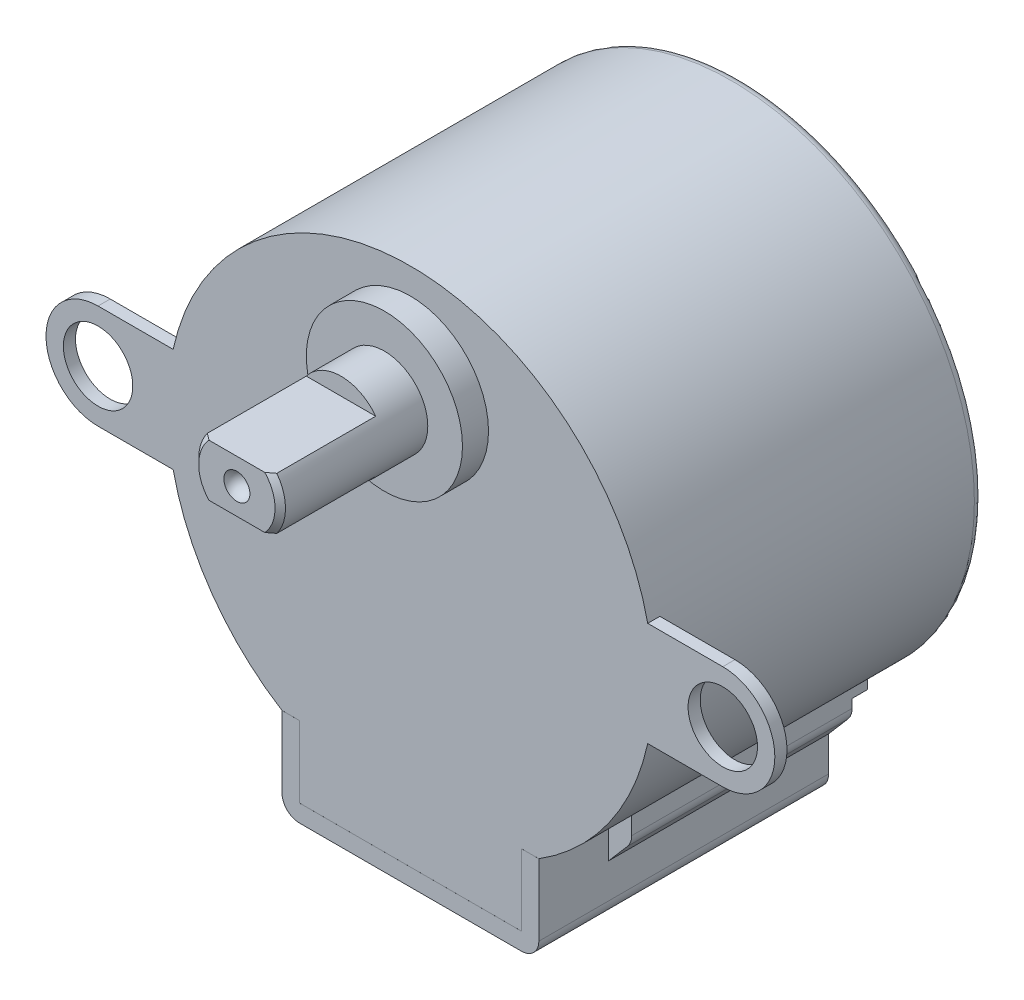
SolidWorks part; units mm, degrees
ref_plane "Ön Düzlem" through (0, 0, 0) normal (0, 0, 1) x (1, 0, 0)
ref_plane "Üst Düzlem" through (0, 0, 0) normal (0, 1, 0) x (1, 0, 0)
ref_plane "Sağ Düzlem" through (0, 0, 0) normal (1, 0, 0) x (0, 0, -1)
sketch "Çizim1" plane through (0, 0, 0) normal (0, 0, 1) x (1, 0, 0)
  circle A0 centre (0, 0) radius 14
  dimension "D1" = 28
extrude "Yükseklik-Ekstrüzyon1" add sketch "Çizim1" along normal blind 19
sketch "Çizim2" plane through (0, 0, 19) normal (0, 0, 1) x (1, 0, 0)
  line L0 (0, 14) -> (0, 8) construction
  circle A0 centre (0, 0) radius 14 construction
  circle A1 centre (0, 8) radius 4.5
  dimension "D2" = 9
  dimension "D1" = 6
extrude "Yükseklik-Ekstrüzyon2" add sketch "Çizim2" along normal blind 1.5
sketch "Çizim3" plane through (0, 0, 20.5) normal (0, 0, 1) x (1, 0, 0)
  circle A0 centre (0, 8) radius 2.5
  dimension "D1" = 5
extrude "Yükseklik-Ekstrüzyon3" add sketch "Çizim3" along normal blind 8.5
sketch "Çizim4" plane through (0, 0, 29) normal (0, 0, 1) x (1, 0, 0)
  line L0 (0, 10.5) -> (0, 9.5) construction
  line L1 (0, 9.5) -> (2.1768, 9.5)
  line L2 (2.1768, 9.5) -> (2.1768, 10.5)
  line L3 (2.1768, 10.5) -> (-2.3997, 10.5)
  line L4 (-2.3997, 10.5) -> (-2.3997, 9.5)
  line L5 (-2.3997, 9.5) -> (0, 9.5)
  line L6 (0, 8) -> (1.2994, 8) construction
  line L7 (2.1768, 5.5) -> (-2.3997, 5.5)
  line L8 (2.1768, 6.5) -> (2.1768, 5.5)
  line L9 (-2.3997, 5.5) -> (-2.3997, 6.5)
  line L10 (-2.3997, 6.5) -> (0, 6.5)
  line L11 (0, 6.5) -> (2.1768, 6.5)
  circle A0 centre (0, 8) radius 2.5 construction
  circle A1 centre (0, 8) radius 2.5 construction
  dimension "D1" = 1
extrude "Kes-Ekstrüzyon1" cut sketch "Çizim4" against normal blind 6
chamfer "Pah1" distance 0.3 angle 45 2 edges at (-2.5, 8, 29) (2.5, 8, 29)
sketch "Çizim5" plane through (0, 0, 29) normal (0, 0, 1) x (1, 0, 0)
  line L0 (0, 8.75) -> (0, 7.25) construction
  line L1 (0, 8.75) -> (0, 7.25)
  arc A0 (0, 7.25) -> (0, 8.75) centre (0, 8) ccw
  dimension "D1" = 1.5
revolve "Kes-Döndür1" cut sketch "Çizim5" angle 360 about L0
sketch "Çizim6" plane through (0, 0, 19) normal (0, 0, 1) x (1, 0, 0)
  line L0 (0, 0) -> (0, -17) construction
  line L1 (0, -17) -> (7.4, -17)
  line L2 (7.4, -17) -> (7.4, -11.8844)
  line L4 (-7.4, -11.8844) -> (-7.4, -17)
  line L5 (-7.4, -17) -> (0, -17)
  arc A0 (-7.4, -11.8844) -> (7.4, -11.8844) centre (0, 0) ccw
  dimension "D1" = 17
  dimension "D2" = 7.4
  dimension "D3" = 7.4
extrude "Yükseklik-Ekstrüzyon4" add sketch "Çizim6" against normal blind 16.7
fillet "Radyus2" radius 1 2 edges at (7.4, -17, 10.65) (-7.4, -17, 10.65)
sketch "Çizim7" plane through (0, 0, 2.3) normal (0, 0, -1) x (-1, 0, 0)
  line L0 (7.4, -14) -> (7.4, -10.9287)
  line L1 (7.4, -11.8844) -> (7.4, -16) construction
  line L2 (7.4, -14) -> (8.75, -14) construction
  line L3 (8.75, -10.9287) -> (8.75, -12.0582)
  line L4 (7.4, -14) -> (8.5085, -12.7098)
  line L5 (7.4, -10.9287) -> (8.75, -10.9287)
  line L6 (0, -17) -> (0, -15.0954) construction
  line L7 (6.4, -17) -> (-6.4, -17) construction
  line L8 (-7.4, -14) -> (-7.4, -10.9287)
  line L9 (-7.4, -10.9287) -> (-8.75, -10.9287)
  line L10 (-8.75, -10.9287) -> (-8.75, -12.0582)
  line L11 (-7.4, -14) -> (-8.5085, -12.7098)
  circle A1 centre (0, 0) radius 14 construction
  arc A2 (8.75, -12.0582) -> (8.5085, -12.7098) centre (7.75, -12.0582) cw
  arc A3 (-8.75, -12.0582) -> (-8.5085, -12.7098) centre (-7.75, -12.0582) ccw
  point P21 (8.75, -12.4287)
  point P24 (-8.75, -12.4287)
  dimension "D1" = 1
  dimension "D2" = 1.35
  dimension "D3" = 1.5
extrude "Yükseklik-Ekstrüzyon5" add sketch "Çizim7" against normal blind 12.7
sketch "Çizim8" plane through (0, 0, 2.3) normal (0, 0, -1) x (-1, 0, 0)
  line L0 (-8.75, -10.9287) -> (-8.75, -11.5623)
  line L1 (8.75, -10.9287) -> (8.75, -11.5623)
  line L4 (1.5, -14.4222) -> (1.5, -13.9194)
  line L5 (-1.5, -14.4222) -> (-1.5, -13.9194)
  arc A0 (-8.75, -11.5623) -> (-1.5, -14.4222) centre (0, 0) ccw
  arc A1 (-8.75, -10.9287) -> (-1.5, -13.9194) centre (0, 0) ccw
  arc A2 (1.5, -13.9194) -> (8.75, -10.9287) centre (0, 0) ccw
  arc A3 (1.5, -14.4222) -> (8.75, -11.5623) centre (0, 0) ccw
  dimension "D1" = 29
extrude "Yükseklik-Ekstrüzyon6" add sketch "Çizim8" along normal blind 0.9
sketch "Çizim9" plane through (0, -17, 0) normal (0, -1, 0) x (1, 0, 0)
  line L0 (0, 19) -> (0, 17) construction
  line L1 (-6.4, 19) -> (6.4, 19) construction
  line L2 (0, 17) -> (3.2, 17) construction
  line L3 (3.2, 17) -> (3.2, 16) construction
  line L4 (3.2, 17) -> (-3.2, 17)
  line L6 (-3.2, 16) -> (3.2, 16)
  arc A0 (3.2, 16) -> (3.2, 17) centre (3.2, 16.5) ccw
  arc A1 (-3.2, 17) -> (-3.2, 16) centre (-3.2, 16.5) ccw
  dimension "D1" = 2
  dimension "D2" = 3.2
  dimension "D3" = 1
  dimension "D4" = 6.4
  dimension "D5" = 6.4
extrude "Kes-Ekstrüzyon2" cut sketch "Çizim9" against normal blind 2.3
fillet "Radyus3" radius 0.5 1 edges at (14, 0, 0)
sketch "Çizim10" plane through (0, 0, 19) normal (0, 0, 1) x (1, 0, 0)
  line L0 (0, 0) -> (0, -3) construction
  line L1 (0, -3) -> (18, -3) construction
  line L2 (18, 3) -> (13.6748, 3)
  line L3 (18, -3) -> (13.6748, -3)
  line L4 (-18, -3) -> (-13.6748, -3)
  line L5 (-18, 3) -> (-13.6748, 3)
  arc A0 (18, -3) -> (18, 3) centre (18, 0) ccw
  circle A1 centre (18, 0) radius 2
  arc A2 (7.4, -11.8844) -> (-7.4, -11.8844) centre (0, 0) ccw construction
  arc A3 (13.6748, -3) -> (13.6748, 3) centre (0, 0) ccw
  arc A4 (-13.6748, -3) -> (-13.6748, 3) centre (0, 0) cw
  circle A5 centre (-18, 0) radius 2
  arc A6 (-18, -3) -> (-18, 3) centre (-18, 0) cw
  dimension "D3" = 4
  dimension "D1" = 3
  dimension "D2" = 18
extrude "Yükseklik-Ekstrüzyon7" add sketch "Çizim10" against normal blind 0.7
sketch "Çizim11" plane through (0, 0, 0) normal (0, 0, -1) x (-1, 0, 0)
  text T0 "28BYJ-48"
extrude "Kes-Ekstrüzyon3" cut sketch "Çizim11" against normal blind 0.3
sketch "Çizim12" plane through (0, 0, 19) normal (0, 0, 1) x (1, 0, 0)
  line L0 (-7.4, -11.8844) -> (-6.4, -11.8844)
  line L1 (-6.4, -11.8844) -> (-6.4, -16)
  line L2 (-6.4, -16) -> (6.4, -16)
  line L3 (6.4, -16) -> (6.4, -11.8844)
  line L4 (6.4, -11.8844) -> (7.4, -11.8844)
  line L5 (7.4, -11.8844) -> (7.4, -16)
  line L6 (6.4, -17) -> (-6.4, -17)
  line L7 (-7.4, -16) -> (-7.4, -11.8844)
  arc A0 (6.4, -17) -> (7.4, -16) centre (6.4, -16) ccw construction
  arc A1 (7.4, -16) -> (6.4, -17) centre (6.4, -16) cw
  arc A2 (-6.4, -17) -> (-7.4, -16) centre (-6.4, -16) cw
extrude "Yükseklik-Ekstrüzyon8" add sketch "Çizim12" along normal blind 0.001
sketch "Sketch2" plane through (0, 0, 0) normal (1, 0, 0) x (0, 0, -1)
  line L0 (-19.001, -17) -> (-2.3, -17) construction
  dimension "D1" = 16.701
sketch "Sketch3" plane through (0, 0, 0) normal (0, 0, 1) x (1, 0, 0)
  line L0 (-6.4, -17) -> (6.4, -17) construction
  line L1 (-6.4, -17) -> (6.4, -17) construction
  line L2 (6.4, -16) -> (-6.4, -16) construction
  line L3 (6.4, -16) -> (-6.4, -16) construction
  line L4 (-6.4, -16) -> (-6.4, -11.8844) construction
  line L5 (-6.4, -16) -> (-6.4, -11.8844) construction
  line L6 (1.6093, 6.5) -> (-1.6093, 6.5) construction
  line L7 (-1.6093, 9.5) -> (1.6093, 9.5) construction
  line L8 (1.6093, 6.5) -> (-1.6093, 6.5)
  line L9 (-1.6093, 9.5) -> (1.6093, 9.5)
  arc A0 (18, -3) -> (18, 3) centre (18, 0) ccw construction
  arc A1 (-18, 3) -> (-18, -3) centre (-18, 0) ccw construction
  arc A2 (13.6748, 3) -> (-13.6748, 3) centre (0, 0) ccw construction
  circle A3 centre (0, 8) radius 4.5 construction
  circle A4 centre (18, 0) radius 2 construction
  circle A5 centre (-18, 0) radius 2 construction
  arc A6 (18, -3) -> (18, 3) centre (18, 0) ccw construction
  arc A7 (-18, 3) -> (-18, -3) centre (-18, 0) ccw construction
  arc A8 (13.6748, 3) -> (-13.6748, 3) centre (0, 0) ccw construction
  circle A9 centre (0, 8) radius 4.5 construction
  circle A10 centre (18, 0) radius 2 construction
  circle A11 centre (-18, 0) radius 2 construction
  circle A14 centre (0, 8) radius 0.75 construction
  arc A15 (1.6093, 6.5) -> (1.6093, 9.5) centre (0, 8) ccw construction
  arc A16 (-1.6093, 9.5) -> (-1.6093, 6.5) centre (0, 8) ccw construction
  circle A17 centre (0, 8) radius 2.5 construction
  circle A18 centre (0, 8) radius 0.75
  arc A19 (1.6093, 6.5) -> (1.6093, 9.5) centre (0, 8) ccw
  arc A20 (-1.6093, 9.5) -> (-1.6093, 6.5) centre (0, 8) ccw
  circle A21 centre (0, 8) radius 2.5
  point P13 (-21, 0)
  point P24 (21, 0)
  dimension "D3" = 4
  dimension "D4" = 9
  dimension "D5" = 14
  dimension "D8" = 5.1156
  dimension "D9" = 5
  dimension "D10" = 1.5
  dimension "D11" = 2.2
  dimension "D1" = 12.8
  dimension "D2" = 42
  dimension "D6" = 7.3252
  dimension "D7" = 4.3252
  dimension "D12" = 3.2187
